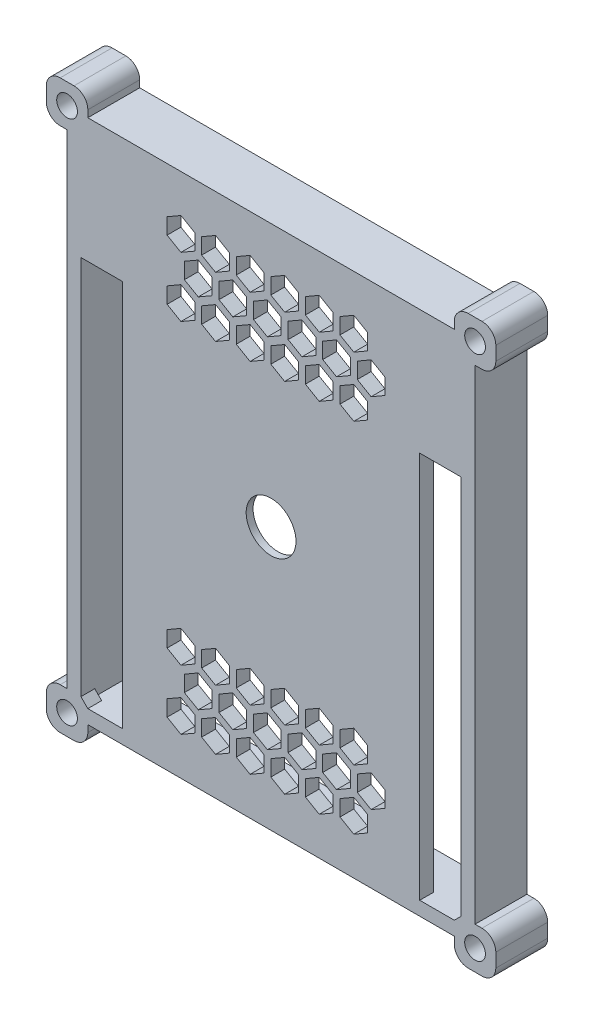
SolidWorks part; units mm, degrees
ref_plane "Front Plane" through (0, 0, 0) normal (0, 0, 1) x (1, 0, 0)
ref_plane "Top Plane" through (0, 0, 0) normal (0, 1, 0) x (1, 0, 0)
ref_plane "Right Plane" through (0, 0, 0) normal (1, 0, 0) x (0, 0, -1)
sketch "Sketch1" plane through (0, 0, 0) normal (0, 0, 1) x (1, 0, 0)
  line L0 (29.5, 35) -> (29.5, -35)
  line L1 (-26.5, 38) -> (-26.5, 39)
  line L2 (-28.5, 41) -> (-30.5, 41)
  line L3 (-32.5, 39) -> (-32.5, 37)
  line L4 (-30.5, 35) -> (-29.5, 35)
  line L5 (30.5, 35) -> (29.5, 35)
  line L6 (32.5, 39) -> (32.5, 37)
  line L7 (28.5, 41) -> (30.5, 41)
  line L8 (26.5, 38) -> (26.5, 39)
  line L9 (26.5, -38) -> (26.5, -39)
  line L10 (28.5, -41) -> (30.5, -41)
  line L11 (32.5, -39) -> (32.5, -37)
  line L12 (30.5, -35) -> (29.5, -35)
  line L13 (-30.5, -35) -> (-29.5, -35)
  line L14 (-32.5, -39) -> (-32.5, -37)
  line L15 (-28.5, -41) -> (-30.5, -41)
  line L16 (-26.5, -38) -> (-26.5, -39)
  line L17 (26.5, -38) -> (-26.5, -38)
  line L18 (-29.5, 35) -> (-29.5, -35)
  line L19 (-26.5, 38) -> (26.5, 38)
  arc A0 (-30.5, 35) -> (-32.5, 37) centre (-30.5, 37) cw
  arc A1 (-32.5, 39) -> (-30.5, 41) centre (-30.5, 39) cw
  arc A2 (-26.5, 39) -> (-28.5, 41) centre (-28.5, 39) ccw
  arc A3 (26.5, 39) -> (28.5, 41) centre (28.5, 39) cw
  arc A4 (32.5, 39) -> (30.5, 41) centre (30.5, 39) ccw
  arc A5 (30.5, 35) -> (32.5, 37) centre (30.5, 37) ccw
  arc A6 (30.5, -35) -> (32.5, -37) centre (30.5, -37) cw
  arc A7 (32.5, -39) -> (30.5, -41) centre (30.5, -39) cw
  arc A8 (26.5, -39) -> (28.5, -41) centre (28.5, -39) ccw
  arc A9 (-26.5, -39) -> (-28.5, -41) centre (-28.5, -39) cw
  arc A10 (-32.5, -39) -> (-30.5, -41) centre (-30.5, -39) ccw
  arc A11 (-30.5, -35) -> (-32.5, -37) centre (-30.5, -37) ccw
  circle A12 centre (-29.5, 38) radius 1.5
  circle A13 centre (29.5, 38) radius 1.5
  circle A14 centre (29.5, -38) radius 1.5
  circle A15 centre (-29.5, -38) radius 1.5
extrude "Boss-Extrude1" add sketch "Sketch1" along normal blind 7.5
sketch "Sketch2" plane through (0, 0, 7.5) normal (0, 0, 1) x (1, 0, 0)
  circle A0 centre (0, 0) radius 3.6
extrude "Cut-Extrude1" cut sketch "Sketch2" against normal up to surface (7.5 mm away) up to face at (31, -38, 0)
sketch "Sketch4" plane through (0, 0, 7.5) normal (0, 0, 1) x (1, 0, 0)
  line L4 (-27.5, -35) -> (-27.5, 20)
  line L5 (-27.5, 20) -> (-21.5, 20)
  line L6 (-21.5, 20) -> (-21.5, -36)
  line L7 (-21.5, -36) -> (-26.5, -36)
  line L8 (-26.5, -36) -> (-27.5, -35)
  line L9 (26.5, -36) -> (27.5, -35)
  line L10 (21.5, -36) -> (26.5, -36)
  line L11 (21.5, 20) -> (21.5, -36)
  line L12 (27.5, 20) -> (21.5, 20)
  line L13 (27.5, -35) -> (27.5, 20)
extrude "Cut-Extrude2" cut sketch "Sketch4" against normal up to surface (7.5 mm away) up to face at (-3.6, 0, 0)
sketch "Sketch5" plane through (0, 0, 0) normal (0, 0, -1) x (-1, 0, 0)
  line L240 (-6.9663, -19.2152) -> (-8.9663, -20.3699)
  line L247 (-8.9663, -20.3699) -> (-8.9663, -22.6793)
  line L248 (-8.9663, -22.6793) -> (-6.9663, -23.834)
  line L249 (-6.9663, -23.834) -> (-4.9663, -22.6793)
  line L250 (-4.9663, -22.6793) -> (-4.9663, -20.3699)
  line L251 (-4.9663, -20.3699) -> (-6.9663, -19.2152)
  line L252 (-1.9663, -19.2152) -> (-3.9663, -20.3699)
  line L259 (-3.9663, -20.3699) -> (-3.9663, -22.6793)
  line L260 (-3.9663, -22.6793) -> (-1.9663, -23.834)
  line L261 (-1.9663, -23.834) -> (0.0337, -22.6793)
  line L262 (0.0337, -22.6793) -> (0.0337, -20.3699)
  line L263 (0.0337, -20.3699) -> (-1.9663, -19.2152)
  line L264 (3.0337, -19.2152) -> (1.0337, -20.3699)
  line L271 (1.0337, -20.3699) -> (1.0337, -22.6793)
  line L272 (1.0337, -22.6793) -> (3.0337, -23.834)
  line L273 (3.0337, -23.834) -> (5.0337, -22.6793)
  line L274 (5.0337, -22.6793) -> (5.0337, -20.3699)
  line L275 (5.0337, -20.3699) -> (3.0337, -19.2152)
  line L276 (8.0337, -19.2152) -> (6.0337, -20.3699)
  line L283 (6.0337, -20.3699) -> (6.0337, -22.6793)
  line L284 (6.0337, -22.6793) -> (8.0337, -23.834)
  line L285 (8.0337, -23.834) -> (10.0337, -22.6793)
  line L286 (10.0337, -22.6793) -> (10.0337, -20.3699)
  line L287 (10.0337, -20.3699) -> (8.0337, -19.2152)
  line L288 (13.0337, -19.2152) -> (11.0337, -20.3699)
  line L295 (11.0337, -20.3699) -> (11.0337, -22.6793)
  line L296 (11.0337, -22.6793) -> (13.0337, -23.834)
  line L297 (13.0337, -23.834) -> (15.0337, -22.6793)
  line L298 (15.0337, -22.6793) -> (15.0337, -20.3699)
  line L299 (15.0337, -20.3699) -> (13.0337, -19.2152)
  line L300 (-6.9663, -27.8752) -> (-8.9663, -29.0299)
  line L301 (-9.4663, -23.5451) -> (-11.4663, -24.6998)
  line L302 (-11.4663, -24.6998) -> (-11.4663, -27.0092)
  line L303 (-11.4663, -27.0092) -> (-9.4663, -28.1639)
  line L304 (-9.4663, -28.1639) -> (-7.4663, -27.0092)
  line L305 (-7.4663, -27.0092) -> (-7.4663, -24.6998)
  line L306 (-7.4663, -24.6998) -> (-9.4663, -23.5451)
  line L307 (-8.9663, -29.0299) -> (-8.9663, -31.3393)
  line L308 (-8.9663, -31.3393) -> (-6.9663, -32.494)
  line L309 (-6.9663, -32.494) -> (-4.9663, -31.3393)
  line L310 (-4.9663, -31.3393) -> (-4.9663, -29.0299)
  line L311 (-4.9663, -29.0299) -> (-6.9663, -27.8752)
  line L312 (-1.9663, -27.8752) -> (-3.9663, -29.0299)
  line L313 (-4.4663, -23.5451) -> (-6.4663, -24.6998)
  line L314 (-6.4663, -24.6998) -> (-6.4663, -27.0092)
  line L315 (-6.4663, -27.0092) -> (-4.4663, -28.1639)
  line L316 (-4.4663, -28.1639) -> (-2.4663, -27.0092)
  line L317 (-2.4663, -27.0092) -> (-2.4663, -24.6998)
  line L318 (-2.4663, -24.6998) -> (-4.4663, -23.5451)
  line L319 (-3.9663, -29.0299) -> (-3.9663, -31.3393)
  line L320 (-3.9663, -31.3393) -> (-1.9663, -32.494)
  line L321 (-1.9663, -32.494) -> (0.0337, -31.3393)
  line L322 (0.0337, -31.3393) -> (0.0337, -29.0299)
  line L323 (0.0337, -29.0299) -> (-1.9663, -27.8752)
  line L324 (3.0337, -27.8752) -> (1.0337, -29.0299)
  line L325 (0.5337, -23.5451) -> (-1.4663, -24.6998)
  line L326 (-1.4663, -24.6998) -> (-1.4663, -27.0092)
  line L327 (-1.4663, -27.0092) -> (0.5337, -28.1639)
  line L328 (0.5337, -28.1639) -> (2.5337, -27.0092)
  line L329 (2.5337, -27.0092) -> (2.5337, -24.6998)
  line L330 (2.5337, -24.6998) -> (0.5337, -23.5451)
  line L331 (1.0337, -29.0299) -> (1.0337, -31.3393)
  line L332 (1.0337, -31.3393) -> (3.0337, -32.494)
  line L333 (3.0337, -32.494) -> (5.0337, -31.3393)
  line L334 (5.0337, -31.3393) -> (5.0337, -29.0299)
  line L335 (5.0337, -29.0299) -> (3.0337, -27.8752)
  line L336 (8.0337, -27.8752) -> (6.0337, -29.0299)
  line L337 (5.5337, -23.5451) -> (3.5337, -24.6998)
  line L338 (3.5337, -24.6998) -> (3.5337, -27.0092)
  line L339 (3.5337, -27.0092) -> (5.5337, -28.1639)
  line L340 (5.5337, -28.1639) -> (7.5337, -27.0092)
  line L341 (7.5337, -27.0092) -> (7.5337, -24.6998)
  line L342 (7.5337, -24.6998) -> (5.5337, -23.5451)
  line L343 (6.0337, -29.0299) -> (6.0337, -31.3393)
  line L344 (6.0337, -31.3393) -> (8.0337, -32.494)
  line L345 (8.0337, -32.494) -> (10.0337, -31.3393)
  line L346 (10.0337, -31.3393) -> (10.0337, -29.0299)
  line L347 (10.0337, -29.0299) -> (8.0337, -27.8752)
  line L348 (13.0337, -27.8752) -> (11.0337, -29.0299)
  line L349 (10.5337, -23.5451) -> (8.5337, -24.6998)
  line L350 (8.5337, -24.6998) -> (8.5337, -27.0092)
  line L351 (8.5337, -27.0092) -> (10.5337, -28.1639)
  line L352 (10.5337, -28.1639) -> (12.5337, -27.0092)
  line L353 (12.5337, -27.0092) -> (12.5337, -24.6998)
  line L354 (12.5337, -24.6998) -> (10.5337, -23.5451)
  line L355 (11.0337, -29.0299) -> (11.0337, -31.3393)
  line L356 (11.0337, -31.3393) -> (13.0337, -32.494)
  line L357 (13.0337, -32.494) -> (15.0337, -31.3393)
  line L358 (15.0337, -31.3393) -> (15.0337, -29.0299)
  line L359 (15.0337, -29.0299) -> (13.0337, -27.8752)
  line L396 (-11.9663, -19.2152) -> (-13.9663, -20.3699)
  line L403 (-13.9663, -20.3699) -> (-13.9663, -22.6793)
  line L404 (-13.9663, -22.6793) -> (-11.9663, -23.834)
  line L405 (-11.9663, -23.834) -> (-9.9663, -22.6793)
  line L406 (-9.9663, -22.6793) -> (-9.9663, -20.3699)
  line L407 (-9.9663, -20.3699) -> (-11.9663, -19.2152)
  line L408 (-11.9663, -27.8752) -> (-13.9663, -29.0299)
  line L409 (-14.4663, -23.5451) -> (-16.4663, -24.6998)
  line L410 (-16.4663, -24.6998) -> (-16.4663, -27.0092)
  line L411 (-16.4663, -27.0092) -> (-14.4663, -28.1639)
  line L412 (-14.4663, -28.1639) -> (-12.4663, -27.0092)
  line L413 (-12.4663, -27.0092) -> (-12.4663, -24.6998)
  line L414 (-12.4663, -24.6998) -> (-14.4663, -23.5451)
  line L415 (-13.9663, -29.0299) -> (-13.9663, -31.3393)
  line L416 (-13.9663, -31.3393) -> (-11.9663, -32.494)
  line L417 (-11.9663, -32.494) -> (-9.9663, -31.3393)
  line L418 (-9.9663, -31.3393) -> (-9.9663, -29.0299)
  line L419 (-9.9663, -29.0299) -> (-11.9663, -27.8752)
  line L435 (-9.9663, 29.0299) -> (-11.9663, 27.8752)
  line L436 (-9.9663, 31.3393) -> (-9.9663, 29.0299)
  line L437 (-11.9663, 32.494) -> (-9.9663, 31.3393)
  line L438 (-13.9663, 31.3393) -> (-11.9663, 32.494)
  line L439 (-13.9663, 29.0299) -> (-13.9663, 31.3393)
  line L440 (-12.4663, 24.6998) -> (-14.4663, 23.5451)
  line L441 (-12.4663, 27.0092) -> (-12.4663, 24.6998)
  line L442 (-14.4663, 28.1639) -> (-12.4663, 27.0092)
  line L443 (-16.4663, 27.0092) -> (-14.4663, 28.1639)
  line L444 (-16.4663, 24.6998) -> (-16.4663, 27.0092)
  line L445 (-14.4663, 23.5451) -> (-16.4663, 24.6998)
  line L446 (-11.9663, 27.8752) -> (-13.9663, 29.0299)
  line L447 (-9.9663, 20.3699) -> (-11.9663, 19.2152)
  line L448 (-9.9663, 22.6793) -> (-9.9663, 20.3699)
  line L449 (-11.9663, 23.834) -> (-9.9663, 22.6793)
  line L450 (-13.9663, 22.6793) -> (-11.9663, 23.834)
  line L451 (-13.9663, 20.3699) -> (-13.9663, 22.6793)
  line L452 (-11.9663, 19.2152) -> (-13.9663, 20.3699)
  line L453 (15.0337, 29.0299) -> (13.0337, 27.8752)
  line L454 (15.0337, 31.3393) -> (15.0337, 29.0299)
  line L455 (13.0337, 32.494) -> (15.0337, 31.3393)
  line L456 (11.0337, 31.3393) -> (13.0337, 32.494)
  line L457 (11.0337, 29.0299) -> (11.0337, 31.3393)
  line L458 (12.5337, 24.6998) -> (10.5337, 23.5451)
  line L459 (12.5337, 27.0092) -> (12.5337, 24.6998)
  line L460 (10.5337, 28.1639) -> (12.5337, 27.0092)
  line L461 (8.5337, 27.0092) -> (10.5337, 28.1639)
  line L462 (8.5337, 24.6998) -> (8.5337, 27.0092)
  line L463 (10.5337, 23.5451) -> (8.5337, 24.6998)
  line L464 (13.0337, 27.8752) -> (11.0337, 29.0299)
  line L465 (10.0337, 29.0299) -> (8.0337, 27.8752)
  line L466 (10.0337, 31.3393) -> (10.0337, 29.0299)
  line L467 (8.0337, 32.494) -> (10.0337, 31.3393)
  line L468 (6.0337, 31.3393) -> (8.0337, 32.494)
  line L469 (6.0337, 29.0299) -> (6.0337, 31.3393)
  line L470 (7.5337, 24.6998) -> (5.5337, 23.5451)
  line L471 (7.5337, 27.0092) -> (7.5337, 24.6998)
  line L472 (5.5337, 28.1639) -> (7.5337, 27.0092)
  line L473 (3.5337, 27.0092) -> (5.5337, 28.1639)
  line L474 (3.5337, 24.6998) -> (3.5337, 27.0092)
  line L475 (5.5337, 23.5451) -> (3.5337, 24.6998)
  line L476 (8.0337, 27.8752) -> (6.0337, 29.0299)
  line L477 (5.0337, 29.0299) -> (3.0337, 27.8752)
  line L478 (5.0337, 31.3393) -> (5.0337, 29.0299)
  line L479 (3.0337, 32.494) -> (5.0337, 31.3393)
  line L480 (1.0337, 31.3393) -> (3.0337, 32.494)
  line L481 (1.0337, 29.0299) -> (1.0337, 31.3393)
  line L482 (2.5337, 24.6998) -> (0.5337, 23.5451)
  line L483 (2.5337, 27.0092) -> (2.5337, 24.6998)
  line L484 (0.5337, 28.1639) -> (2.5337, 27.0092)
  line L485 (-1.4663, 27.0092) -> (0.5337, 28.1639)
  line L486 (-1.4663, 24.6998) -> (-1.4663, 27.0092)
  line L487 (0.5337, 23.5451) -> (-1.4663, 24.6998)
  line L488 (3.0337, 27.8752) -> (1.0337, 29.0299)
  line L489 (0.0337, 29.0299) -> (-1.9663, 27.8752)
  line L490 (0.0337, 31.3393) -> (0.0337, 29.0299)
  line L491 (-1.9663, 32.494) -> (0.0337, 31.3393)
  line L492 (-3.9663, 31.3393) -> (-1.9663, 32.494)
  line L493 (-3.9663, 29.0299) -> (-3.9663, 31.3393)
  line L494 (-2.4663, 24.6998) -> (-4.4663, 23.5451)
  line L495 (-2.4663, 27.0092) -> (-2.4663, 24.6998)
  line L496 (-4.4663, 28.1639) -> (-2.4663, 27.0092)
  line L497 (-6.4663, 27.0092) -> (-4.4663, 28.1639)
  line L498 (-6.4663, 24.6998) -> (-6.4663, 27.0092)
  line L499 (-4.4663, 23.5451) -> (-6.4663, 24.6998)
  line L500 (-1.9663, 27.8752) -> (-3.9663, 29.0299)
  line L501 (-4.9663, 29.0299) -> (-6.9663, 27.8752)
  line L502 (-4.9663, 31.3393) -> (-4.9663, 29.0299)
  line L503 (-6.9663, 32.494) -> (-4.9663, 31.3393)
  line L504 (-8.9663, 31.3393) -> (-6.9663, 32.494)
  line L505 (-8.9663, 29.0299) -> (-8.9663, 31.3393)
  line L506 (-7.4663, 24.6998) -> (-9.4663, 23.5451)
  line L507 (-7.4663, 27.0092) -> (-7.4663, 24.6998)
  line L508 (-9.4663, 28.1639) -> (-7.4663, 27.0092)
  line L509 (-11.4663, 27.0092) -> (-9.4663, 28.1639)
  line L510 (-11.4663, 24.6998) -> (-11.4663, 27.0092)
  line L511 (-9.4663, 23.5451) -> (-11.4663, 24.6998)
  line L512 (-6.9663, 27.8752) -> (-8.9663, 29.0299)
  line L513 (15.0337, 20.3699) -> (13.0337, 19.2152)
  line L514 (15.0337, 22.6793) -> (15.0337, 20.3699)
  line L515 (13.0337, 23.834) -> (15.0337, 22.6793)
  line L516 (11.0337, 22.6793) -> (13.0337, 23.834)
  line L517 (11.0337, 20.3699) -> (11.0337, 22.6793)
  line L518 (13.0337, 19.2152) -> (11.0337, 20.3699)
  line L519 (10.0337, 20.3699) -> (8.0337, 19.2152)
  line L520 (10.0337, 22.6793) -> (10.0337, 20.3699)
  line L521 (8.0337, 23.834) -> (10.0337, 22.6793)
  line L522 (6.0337, 22.6793) -> (8.0337, 23.834)
  line L523 (6.0337, 20.3699) -> (6.0337, 22.6793)
  line L524 (8.0337, 19.2152) -> (6.0337, 20.3699)
  line L525 (5.0337, 20.3699) -> (3.0337, 19.2152)
  line L526 (5.0337, 22.6793) -> (5.0337, 20.3699)
  line L527 (3.0337, 23.834) -> (5.0337, 22.6793)
  line L528 (1.0337, 22.6793) -> (3.0337, 23.834)
  line L529 (1.0337, 20.3699) -> (1.0337, 22.6793)
  line L530 (3.0337, 19.2152) -> (1.0337, 20.3699)
  line L531 (0.0337, 20.3699) -> (-1.9663, 19.2152)
  line L532 (0.0337, 22.6793) -> (0.0337, 20.3699)
  line L533 (-1.9663, 23.834) -> (0.0337, 22.6793)
  line L534 (-3.9663, 22.6793) -> (-1.9663, 23.834)
  line L535 (-3.9663, 20.3699) -> (-3.9663, 22.6793)
  line L536 (-1.9663, 19.2152) -> (-3.9663, 20.3699)
  line L537 (-4.9663, 20.3699) -> (-6.9663, 19.2152)
  line L538 (-4.9663, 22.6793) -> (-4.9663, 20.3699)
  line L539 (-6.9663, 23.834) -> (-4.9663, 22.6793)
  line L540 (-8.9663, 22.6793) -> (-6.9663, 23.834)
  line L541 (-8.9663, 20.3699) -> (-8.9663, 22.6793)
  line L542 (-6.9663, 19.2152) -> (-8.9663, 20.3699)
  circle A0 centre (-14.4663, 25.8545) radius 2 construction
  circle A1 centre (10.5337, 25.8545) radius 2 construction
  circle A2 centre (5.5337, 25.8545) radius 2 construction
  circle A3 centre (0.5337, 25.8545) radius 2 construction
  circle A4 centre (-4.4663, 25.8545) radius 2 construction
  circle A5 centre (-9.4663, 25.8545) radius 2 construction
  circle A26 centre (-9.4663, -25.8545) radius 2 construction
  circle A27 centre (-4.4663, -25.8545) radius 2 construction
  circle A28 centre (0.5337, -25.8545) radius 2 construction
  circle A29 centre (5.5337, -25.8545) radius 2 construction
  circle A30 centre (10.5337, -25.8545) radius 2 construction
  circle A35 centre (-14.4663, -25.8545) radius 2 construction
extrude "Cut-Extrude3" cut sketch "Sketch5" against normal up to surface (7.5 mm away) up to face at (-24.9, -13.4, 7.5)
sketch "Sketch8" plane through (0, 0, 0) normal (0, 0, -1) x (-1, 0, 0)
  line L1 (-27.5, -36) -> (27.5, -36)
  line L2 (-27.5, -36) -> (-27.5, 36)
  line L3 (-27.5, 36) -> (27.5, 36)
  line L4 (27.5, -36) -> (27.5, 36)
  line L5 (-27.5, -36) -> (27.5, 36) construction
  line L6 (-27.5, 36) -> (27.5, -36) construction
  point P0 (0, 0)
  dimension "D1" = 55
  dimension "D2" = 72
extrude "Cut-Extrude9" cut sketch "Sketch8" against normal blind 5.5
sketch "Sketch9" plane through (0, 0, 5.5) normal (0, 0, -1) x (-1, 0, 0)
  line L10 (0, 9.8) -> (-8.5, 9.8)
  line L11 (-12.8, 5.5) -> (-12.8, -10.5)
  line L17 (-8.5, -14.8) -> (8.5, -14.8)
  line L18 (12.8, -10.5) -> (12.8, 5.5)
  line L19 (0, 9.8) -> (8.5, 9.8)
  line L20 (-8.5, 9.8) -> (-10.8, 9.8)
  line L21 (-12.8, 7.8) -> (-12.8, 5.5)
  line L22 (-12.8, -10.5) -> (-12.8, -12.8)
  line L23 (-10.8, -14.8) -> (-8.5, -14.8)
  line L24 (8.5, -14.8) -> (10.8, -14.8)
  line L25 (12.8, -12.8) -> (12.8, -10.5)
  line L26 (8.5, 9.8) -> (10.8, 9.8)
  line L27 (12.8, 7.8) -> (12.8, 5.5)
  arc A16 (12.8, 7.8) -> (10.8, 9.8) centre (10.8, 7.8) ccw
  arc A17 (12.8, -12.8) -> (10.8, -14.8) centre (10.8, -12.8) cw
  arc A18 (-10.8, -14.8) -> (-12.8, -12.8) centre (-10.8, -12.8) cw
  arc A19 (-12.8, 7.8) -> (-10.8, 9.8) centre (-10.8, 7.8) cw
  dimension "D1" = 2
extrude "Cut-Extrude10" cut sketch "Sketch9" against normal blind 1
sketch "Sketch12" plane through (0, 0, 6.5) normal (0, 0, -1) x (-1, 0, 0)
  line L3 (-11.75, -1.25) -> (-9.25, -1.25)
  line L4 (-11.75, -1.25) -> (-11.75, 1.25)
  line L5 (-11.75, 1.25) -> (-9.25, 1.25)
  line L6 (-9.25, -1.25) -> (-9.25, 1.25)
  line L7 (9.25, -1.25) -> (9.25, 1.25)
  line L8 (11.75, 1.25) -> (9.25, 1.25)
  line L9 (11.75, -1.25) -> (11.75, 1.25)
  line L10 (11.75, -1.25) -> (9.25, -1.25)
  line L32 (11.75, -11.25) -> (9.25, -11.25)
  line L33 (11.75, -11.25) -> (11.75, -13.75)
  line L34 (11.75, -13.75) -> (9.25, -13.75)
  line L35 (9.25, -11.25) -> (9.25, -13.75)
  line L36 (-9.25, -11.25) -> (-9.25, -13.75)
  line L37 (-11.75, -13.75) -> (-9.25, -13.75)
  line L38 (-11.75, -11.25) -> (-11.75, -13.75)
  line L39 (-11.75, -11.25) -> (-9.25, -11.25)
extrude "Boss-Extrude2" add sketch "Sketch12" along normal blind 3
sketch "Sketch13" plane through (0, 0, 3.5) normal (0, 0, -1) x (-1, 0, 0)
  circle A0 centre (-10.5, 0) radius 1
  circle A1 centre (10.5, 0) radius 1
  circle A4 centre (10.5, -12.5) radius 1
  circle A5 centre (-10.5, -12.5) radius 1
extrude "Boss-Extrude3" add sketch "Sketch13" along normal blind 2
